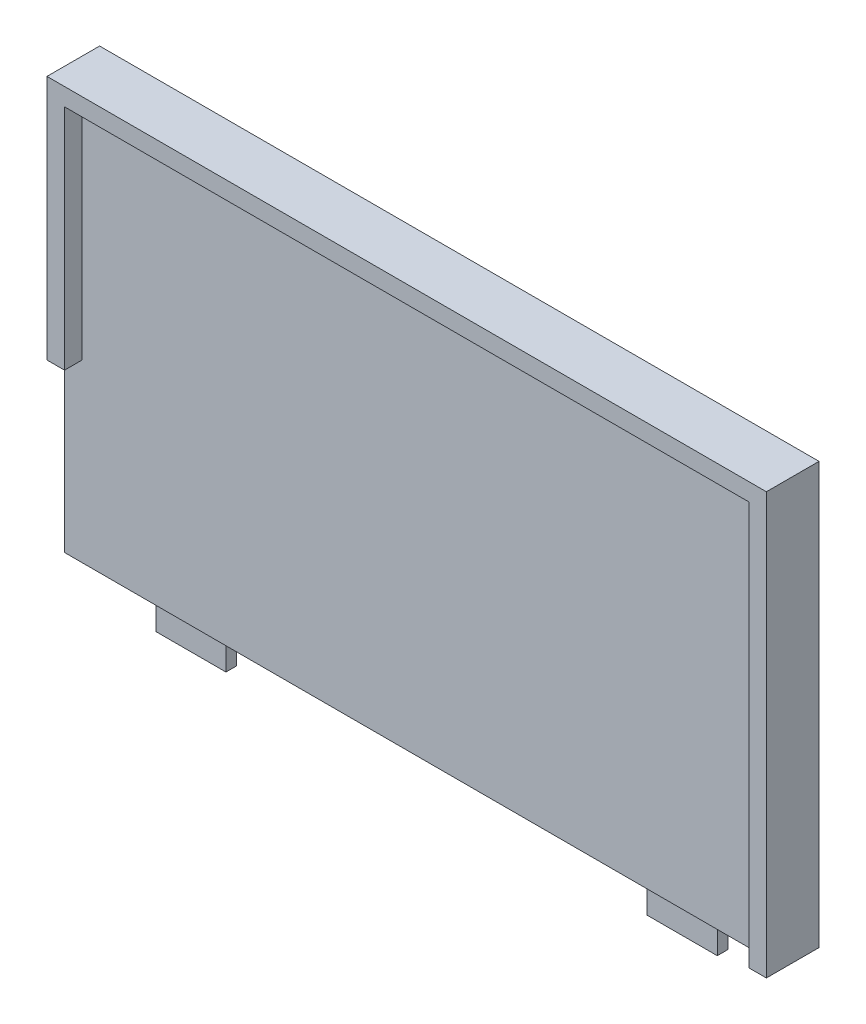
SolidWorks part; units mm, degrees
ref_plane "Front Plane" through (0, 0, 0) normal (1, 0, 0) x (0, 1, 0)
ref_plane "Top Plane" through (0, 0, 0) normal (0, 0, 1) x (0, 1, 0)
ref_plane "Right Plane" through (0, 0, 0) normal (0, 1, 0) x (-1, 0, 0)
sketch "Sketch1" plane through (0, 0, 0) normal (0, 0, 1) x (0, 1, 0)
  line L1 (-60, -102.5) -> (60, -102.5)
  line L2 (-60, -102.5) -> (-60, 102.5)
  line L3 (-60, 102.5) -> (60, 102.5)
  line L4 (60, -102.5) -> (60, 102.5)
  line L5 (-60, -102.5) -> (60, 102.5) construction
  line L6 (-60, 102.5) -> (60, -102.5) construction
  point P0 (0, 0)
  dimension "D1" = 205
  dimension "D2" = 120
extrude "Boss-Extrude1" add sketch "Sketch1" along normal blind 10
sketch "Sketch2" plane through (0, 0, 10) normal (0, 0, 1) x (1, 0, 0)
  line L0 (102.5, -60) -> (97.5, -60)
  line L1 (-102.5, -60) -> (102.5, -60) construction
  line L2 (97.5, -60) -> (97.5, 55)
  line L3 (97.5, 55) -> (-97.5, 55)
  line L8 (-102.5, 60) -> (102.5, 60)
  line L9 (102.5, 60) -> (102.5, -60)
  line L10 (-102.5, 60) -> (-102.5, -10)
  line L11 (-102.5, -10) -> (-97.5, -10)
  line L12 (-97.5, -10) -> (-97.5, 55)
  dimension "D1" = 5
  dimension "D2" = 5
  dimension "D3" = 5
  dimension "D4" = 50
extrude "Boss-Extrude2" add sketch "Sketch2" along normal blind 5
sketch "Sketch3" plane through (-102.5, 0, 0) normal (-1, 0, 0) x (0, -1, 0)
  line L0 (60, 10) -> (60, 0) construction
  line L1 (19.75, 3.25) -> (40.25, 3.25)
  line L2 (19.75, 3.25) -> (19.75, 6.75)
  line L3 (19.75, 6.75) -> (40.25, 6.75)
  line L4 (40.25, 3.25) -> (40.25, 6.75)
  line L5 (19.75, 3.25) -> (40.25, 6.75) construction
  line L6 (19.75, 6.75) -> (40.25, 3.25) construction
  line L7 (-60, 0) -> (60, 0) construction
  point P0 (30, 5)
  dimension "D1" = 30
  dimension "D2" = 20.5
  dimension "D3" = 3.5
  dimension "D4" = 5
extrude "Cut-Extrude1" cut sketch "Sketch3" against normal blind 10
sketch "Sketch4" plane through (0, -60, 0) normal (0, -1, 0) x (1, 0, 0)
  line L0 (-102.5, 0) -> (102.5, 0) construction
  line L1 (-80, 3.4963) -> (-60, 3.4963)
  line L2 (-80, 3.4963) -> (-80, 6.4963)
  line L3 (-80, 6.4963) -> (-60, 6.4963)
  line L4 (-60, 3.4963) -> (-60, 6.4963)
  line L5 (-80, 3.4963) -> (-60, 6.4963) construction
  line L6 (-80, 6.4963) -> (-60, 3.4963) construction
  line L11 (0, -1000) -> (0, 49000) construction
  line L12 (80, 6.4963) -> (60, 3.4963) construction
  line L13 (80, 3.4963) -> (60, 6.4963) construction
  line L14 (60, 3.4963) -> (60, 6.4963)
  line L15 (80, 6.4963) -> (60, 6.4963)
  line L16 (80, 3.4963) -> (80, 6.4963)
  line L17 (80, 3.4963) -> (60, 3.4963)
  point P0 (-70, 4.9963)
  point P14 (70, 4.9963)
  dimension "D1" = 4.9963
  dimension "D2" = 20
  dimension "D3" = 3
  dimension "D4" = 70
extrude "Boss-Extrude3" add sketch "Sketch4" along normal blind 10
